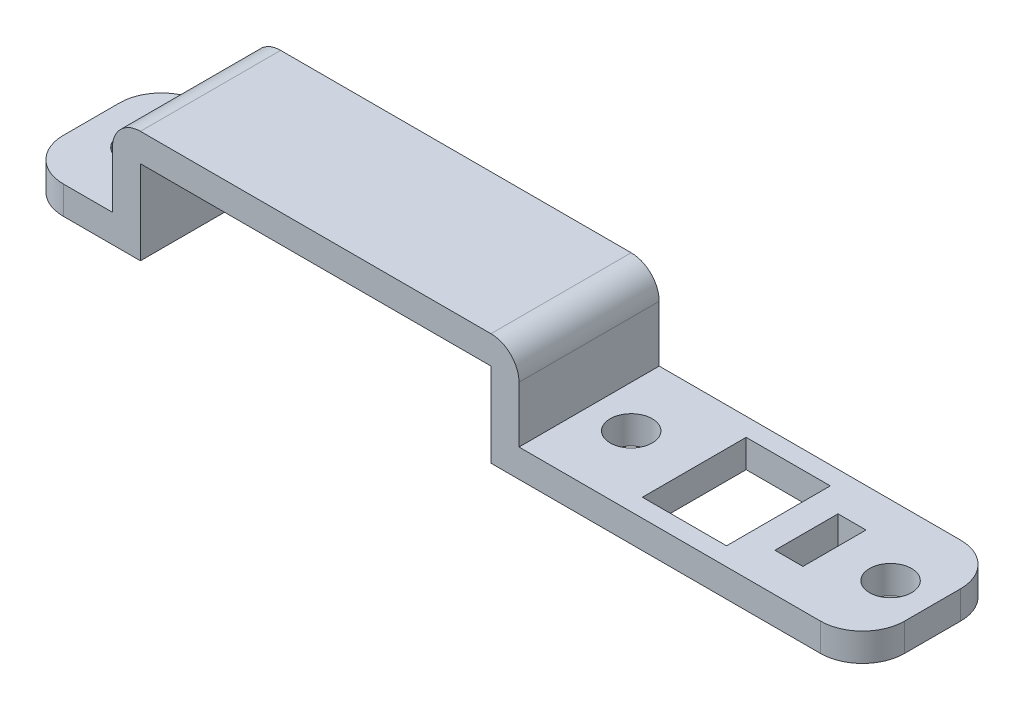
SolidWorks part; units mm, degrees
ref_plane "Alzado" through (0, 0, 0) normal (0, 0, 1) x (1, 0, 0)
ref_plane "Planta" through (0, 0, 0) normal (0, 1, 0) x (1, 0, 0)
ref_plane "Vista lateral" through (0, 0, 0) normal (1, 0, 0) x (0, 0, -1)
sketch "Croquis1" plane through (0, 0, 0) normal (0, 0, 1) x (1, 0, 0)
  line L0 (0, 0) -> (7.5, 0)
  line L5 (7.5, 0) -> (7.5, 6)
  line L6 (7.5, 6) -> (32.5, 6)
  line L7 (32.5, 6) -> (32.5, 0)
  line L8 (32.5, 0) -> (41.5, 0)
  line L9 (0, 0) -> (-1, 0)
  line L12 (41.5, 0) -> (59, 0)
  dimension "D1" = 59
  dimension "D2" = 7.5
  dimension "D3" = 25
  dimension "D4" = 9
  dimension "D5" = 1
  dimension "D6" = 6
extrude "Extruir-Lámina1" add sketch "Croquis1" against normal blind 10 thin thin type one direction reverse wall 2
sketch "Croquis2" plane through (0, 2, 0) normal (0, 1, 0) x (1, 0, 0)
  line L0 (-1, 5) -> (59, 5) construction
  line L1 (-1, 10) -> (-1, 0) construction
  line L2 (59, 10) -> (59, 0) construction
  line L3 (7.5, 10) -> (7.5, 0) construction
  line L4 (7.5, 10) -> (7.5, 0) construction
  circle A0 centre (2.5, 5) radius 1.5
  circle A1 centre (37.5, 5) radius 1.5
  circle A2 centre (56, 5) radius 1.5
  dimension "D1" = 3
  dimension "D2" = 5
  dimension "D3" = 35
  dimension "D4" = 18.5
extrude "Cortar-Extruir1" cut sketch "Croquis2" against normal through all
fillet "Redondeo2" radius 3 4 edges at (-1, 1, -10) (-1, 1, 0) (59, 1, -10) (59, 1, 0)
fillet "Redondeo3" radius 2 2 edges at (34.5, 8, -5) (5.5, 8, -5)
sketch "Croquis3" plane through (0, 2, 0) normal (0, 1, 0) x (1, 0, 0)
  line L0 (59, 5) -> (34.5, 5) construction
  line L1 (59, 7) -> (59, 3) construction
  line L2 (34.5, 10) -> (34.5, 0) construction
  line L4 (42, 8.7) -> (48, 8.7)
  line L5 (42, 8.7) -> (42, 1.3)
  line L6 (42, 1.3) -> (48, 1.3)
  line L7 (48, 8.7) -> (48, 1.3)
  line L8 (50, 7.25) -> (52, 7.25)
  line L9 (50, 7.25) -> (50, 2.75)
  line L10 (50, 2.75) -> (52, 2.75)
  line L11 (52, 7.25) -> (52, 2.75)
  point P14 (42, 5)
  point P15 (37.5, 5)
  point P16 (50, 5)
  dimension "D1" = 6
  dimension "D2" = 7.4
  dimension "D3" = 4.5
  dimension "D4" = 2
  dimension "D5" = 2
  dimension "D6" = 4.5
extrude "Cortar-Extruir2" cut sketch "Croquis3" against normal through all
sketch "Croquis4" plane through (0, 8, 0) normal (0, 1, 0) x (1, 0, 0)
  line L1 (21.5, 6.75) -> (31.5, 6.75)
  line L2 (21.5, 6.75) -> (21.5, 3.75)
  line L3 (21.5, 3.75) -> (31.5, 3.75)
  line L4 (7.5, 0) -> (32.5, 0)
  line L5 (32.5, 0) -> (32.5, 10)
  line L6 (32.5, 10) -> (7.5, 10)
  line L7 (7.5, 10) -> (7.5, 0)
  line L9 (32.5, 0) -> (32.5, 10) construction
  line L12 (31.5, 6.75) -> (31.5, 3.75)
  point P8 (26.5, 6.75)
  dimension "D2" = 6
  dimension "D3" = 10
  dimension "D4" = 3
  dimension "D5" = 3.25
  dimension "D1" = 0
extrude "Saliente-Extruir1" [suppressed] add sketch "Croquis4" along normal blind 10
fillet "Redondeo4" [suppressed] radius 3
sketch "Croquis6" [suppressed] plane through (0, 0, -3.75) normal (0, 0, 1) x (1, 0, 0)
  line L4 (31.5, 18) -> (21.5, 18)
  line L5 (21.5, 18) -> (21.5, 8)
  line L6 (21.5, 8) -> (31.5, 8)
  line L7 (31.5, 8) -> (31.5, 18)
  line L8 (31.5, 18) -> (21.5, 18) construction
  line L9 (21.5, 18) -> (21.5, 8) construction
  line L10 (21.5, 8) -> (31.5, 8) construction
  line L11 (31.5, 8) -> (31.5, 18) construction
  circle A0 centre (26.5, 13) radius 3.25
  point P0 (26.5, 13)
  dimension "D4" = 6.5
  dimension "D2" = 5
  dimension "D3" = 5
  dimension "D1" = 0
extrude "Cortar-Extruir3" [suppressed] cut sketch "Croquis6" against normal blind 10
